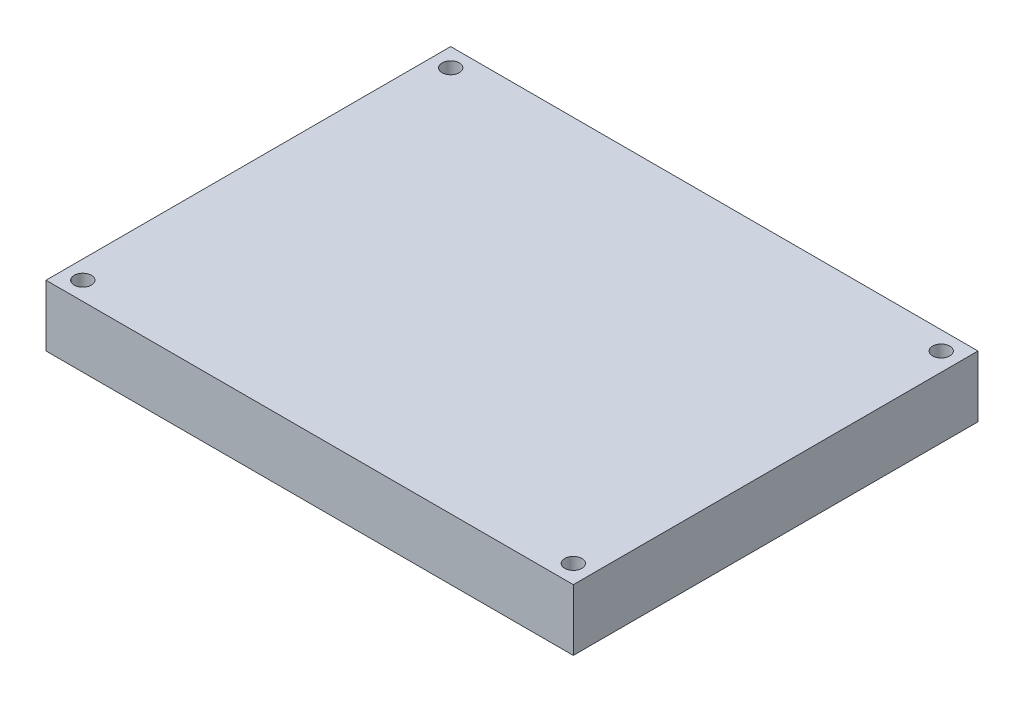
SolidWorks part; units mm, degrees
material "ABS"
ref_plane "前视基准面" through (0, 0, 0) normal (0, 0, 1) x (1, 0, 0)
ref_plane "上视基准面" through (0, 0, 0) normal (0, 1, 0) x (1, 0, 0)
ref_plane "右视基准面" through (0, 0, 0) normal (1, 0, 0) x (0, 0, -1)
sketch "草图1" plane through (0, 0, 0) normal (0, 1, 0) x (1, 0, 0)
  line L1 (-43, 33) -> (43, 33)
  line L2 (-43, 33) -> (-43, -33)
  line L3 (-43, -33) -> (43, -33)
  line L4 (43, 33) -> (43, -33)
  line L5 (0, -33) -> (0, 33) construction
  line L6 (-43, 0) -> (43, 0) construction
  point P0 (0, 0)
  dimension "D1" = 86
  dimension "D2" = 66
extrude "凸台-拉伸1" add sketch "草图1" along normal blind 10
sketch "草图2" plane through (0, 10, 0) normal (0, 1, 0) x (1, 0, 0)
  line L0 (0, 33.5288) -> (0, -22.1952) construction
  line L1 (-29.9533, 0) -> (27.5247, 0) construction
  circle A0 centre (-40, 30) radius 1.4
  circle A1 centre (40, 30) radius 1.4
  circle A2 centre (40, -30) radius 1.4
  circle A3 centre (-40, -30) radius 1.4
  dimension "D1" = 2.8
  dimension "D2" = 80
  dimension "D3" = 60
extrude "切除-拉伸1" cut sketch "草图2" against normal through all
sketch "草图4" plane through (0, 10, 0) normal (0, 1, 0) x (1, 0, 0)
  line L0 (43, -33) -> (43, 33) construction
  line L1 (43, 0) -> (31.4753, 0)
  line L2 (43, 0) -> (43, -20.6338)
  line L3 (43, -20.6338) -> (31.4753, -20.6338)
  line L4 (31.4753, 0) -> (31.4753, -20.6338)
  line L5 (-43, 33) -> (-43, -33) construction
  line L6 (-43, 22.499) -> (-34.2731, 22.499)
  line L7 (-43, 22.499) -> (-43, 0)
  line L8 (-43, 0) -> (-34.2731, 0)
  line L9 (-34.2731, 22.499) -> (-34.2731, 0)
  line L10 (43, 33) -> (-43, 33) construction
  line L11 (-29.1438, 33) -> (-10.2586, 33)
  line L12 (-29.1438, 33) -> (-29.1438, 19.7012)
  line L13 (-29.1438, 19.7012) -> (-10.2586, 19.7012)
  line L14 (-10.2586, 33) -> (-10.2586, 19.7012)
  line L16 (19.1183, 0) -> (25.4134, 0)
  line L17 (19.1183, 0) -> (19.1183, -20.6338)
  line L18 (19.1183, -20.6338) -> (25.4134, -20.6338)
  line L19 (25.4134, 0) -> (25.4134, -20.6338)
  line L20 (-43, -3.847) -> (-34.2731, -3.847)
  line L21 (-43, -3.847) -> (-43, -18.0691)
  line L22 (-43, -18.0691) -> (-34.2731, -18.0691)
  line L23 (-34.2731, -3.847) -> (-34.2731, -18.0691)
  line L24 (-19.7012, 5.2459) -> (3.9636, 5.2459)
  line L25 (-19.7012, 5.2459) -> (-19.7012, -6.8779)
  line L26 (-19.7012, -6.8779) -> (3.9636, -6.8779)
  line L27 (3.9636, 5.2459) -> (3.9636, -6.8779)
  line L28 (43, 22.499) -> (33.1073, 22.499)
  line L29 (43, 22.499) -> (43, 11.2495)
  line L30 (43, 11.2495) -> (33.1073, 11.2495)
  line L31 (33.1073, 22.499) -> (33.1073, 11.2495)
